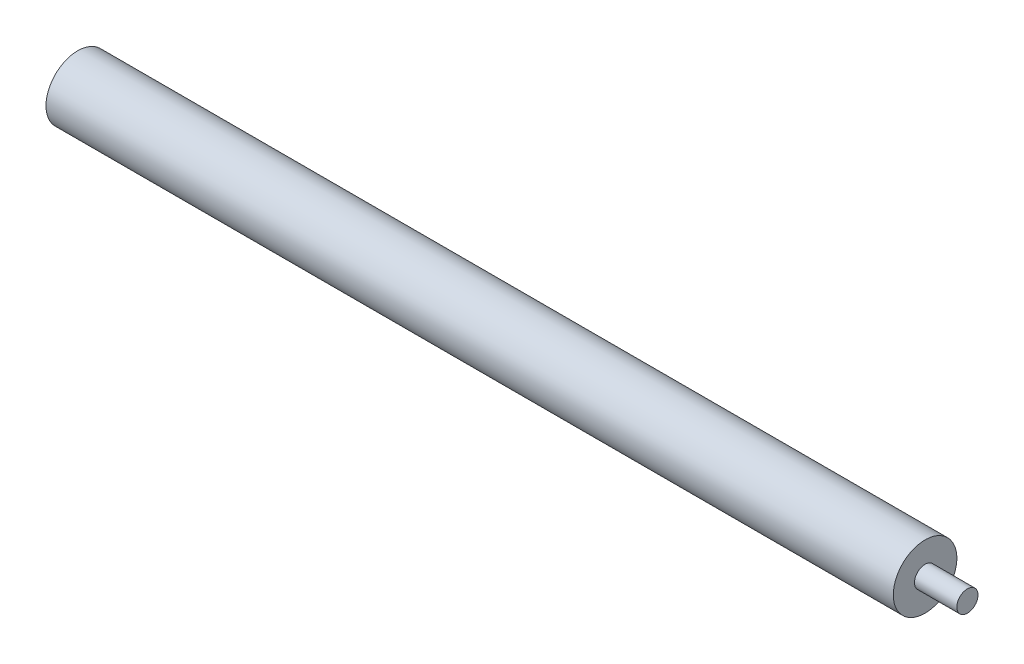
SolidWorks part; units mm, degrees
material "Custom Plastic"
ref_plane "Front Plane" through (0, 0, 0) normal (0, 0, 1) x (1, 0, 0)
ref_plane "Top Plane" through (0, 0, 0) normal (0, 1, 0) x (1, 0, 0)
ref_plane "Right Plane" through (0, 0, 0) normal (1, 0, 0) x (0, 0, -1)
other "Configuration Table"
sketch "Sketch1" plane through (0, 0, 0) normal (0, 0, 1) x (1, 0, 0)
  line L0 (-54.1663, 0) -> (-47.8163, 0) construction
  line L1 (-266.7, 0) -> (-266.7, 9.525)
  line L2 (-266.7, 9.525) -> (-12.7, 9.525)
  line L3 (-12.7, 9.525) -> (-12.7, 3.175)
  line L4 (-12.7, 3.175) -> (0, 3.175)
  line L5 (0, 3.175) -> (0, 0)
  line L6 (0, 0) -> (-266.7, 0)
  dimension "D1" = 19.05
  dimension "D2" = 6.35
  dimension "D3" = 254
  dimension "D4" = 12.7
revolve "Revolve1" add sketch "Sketch1" angle 360 about L0
sketch "Sketch2" plane through (-266.7, 0, 0) normal (-1, 0, 0) x (0, 0, 1)
  circle A0 centre (0, 0) radius 0.7937
  dimension "D1" = 1.5875
extrude "Cut-Extrude1" cut sketch "Sketch2" against normal blind 12.7
